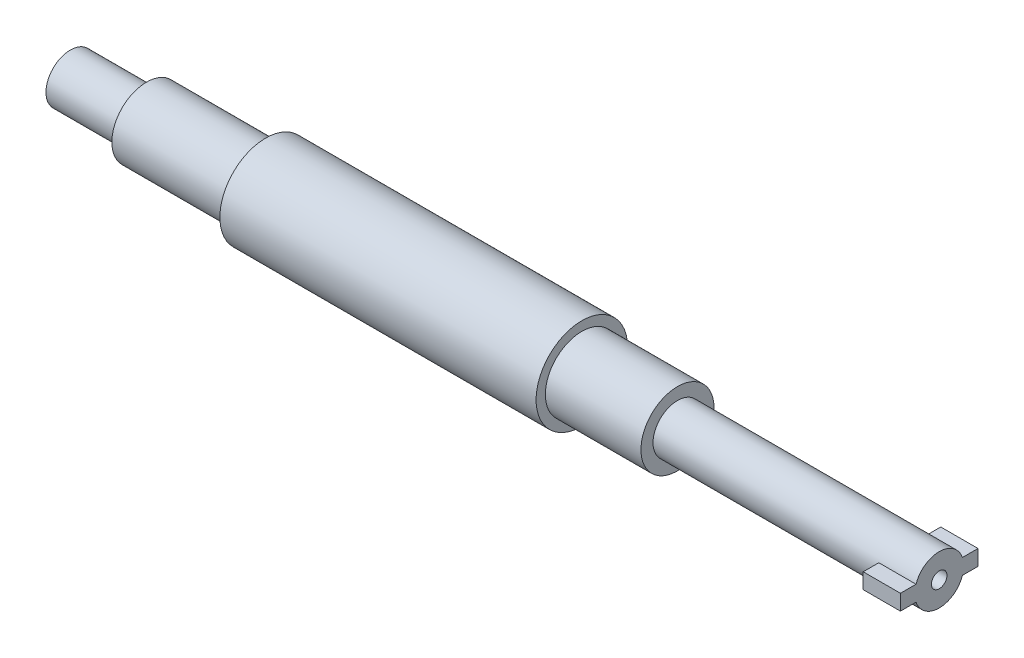
SolidWorks part; units mm, degrees
ref_plane "Front Plane" through (0, 0, 0) normal (0, 0, 1) x (1, 0, 0)
ref_plane "Top Plane" through (0, 0, 0) normal (0, 1, 0) x (1, 0, 0)
ref_plane "Right Plane" through (0, 0, 0) normal (1, 0, 0) x (0, 0, -1)
sketch "Sketch1" plane through (0, 0, 0) normal (1, 0, 0) x (0, 0, -1)
  circle A0 centre (0, 0) radius 5
extrude "Shaft" add sketch "Sketch1" along normal blind 177.8
sketch "Sketch2" plane through (177.8, 0, 0) normal (1, 0, 0) x (0, 0, -1)
  line L1 (7.9375, -1.5875) -> (-7.9375, -1.5875)
  line L2 (7.9375, -1.5875) -> (7.9375, 1.5875)
  line L3 (7.9375, 1.5875) -> (-7.9375, 1.5875)
  line L4 (-7.9375, -1.5875) -> (-7.9375, 1.5875)
  line L5 (7.9375, -1.5875) -> (-7.9375, 1.5875) construction
  line L6 (7.9375, 1.5875) -> (-7.9375, -1.5875) construction
  point P0 (0, 0)
extrude "Shaft Key Male" add sketch "Sketch2" against normal blind 7.62
sketch "Sketch3" plane through (177.8, 0, 0) normal (1, 0, 0) x (0, 0, -1)
  circle A0 centre (0, 0) radius 1.5875
extrude "Bolt Bore" cut sketch "Sketch3" against normal blind 50.8
sketch "Sketch4" plane through (0, 0, 0) normal (-1, 0, 0) x (0, 0, 1)
  circle A0 centre (0, 0) radius 4
extrude "Cut-Extrude1" cut sketch "Sketch4" against normal blind 25.4
sketch "Sketch5" plane through (0, 0, 0) normal (0, 1, 0) x (1, 0, 0)
  line L0 (144.0552, 0) -> (15.5785, 0)
  line L1 (15.5785, 0) -> (15.5785, -7.0967)
  line L2 (15.5785, -7.0967) -> (39.9579, -7.0967)
  line L3 (39.9579, -7.0967) -> (39.9579, -9.3677)
  line L4 (39.9579, -9.3677) -> (104.6702, -9.3677)
  line L5 (104.6702, -9.3677) -> (104.6702, -7.4752)
  line L6 (104.6702, -7.4752) -> (124.2365, -7.4752)
  line L7 (124.2365, -7.4752) -> (124.2365, -5)
  line L8 (0, -5) -> (170.18, -5) construction
  line L9 (124.2365, -5) -> (144.0552, -5)
  line L10 (144.0552, -5) -> (144.0552, 0)
  point P9 (124.2365, -5)
revolve "Revolve1" add sketch "Sketch5" angle 360 about L0
